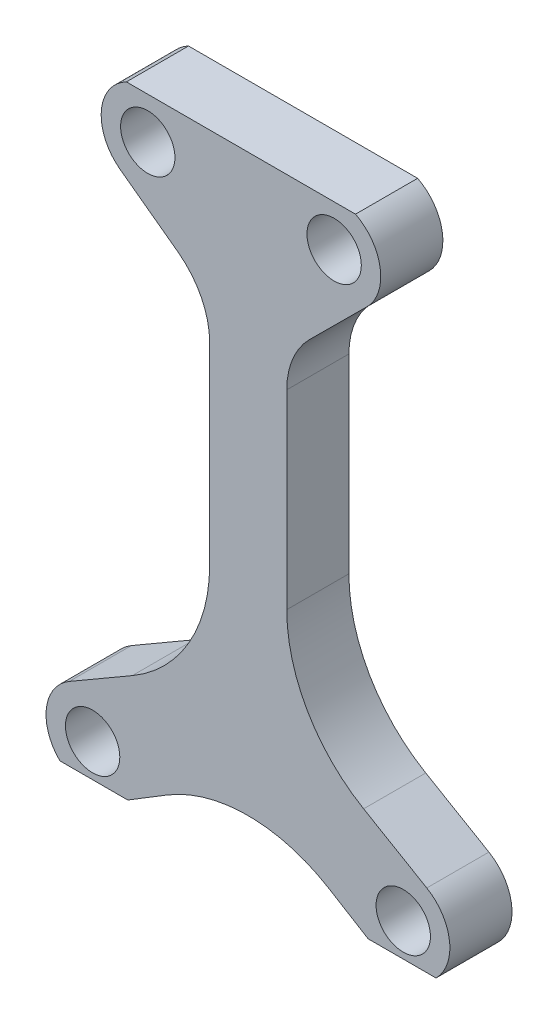
SolidWorks part; units mm, degrees
ref_plane "前视基准面" through (0, 0, 0) normal (0, 0, 1) x (1, 0, 0)
ref_plane "上视基准面" through (0, 0, 0) normal (0, 1, 0) x (1, 0, 0)
ref_plane "右视基准面" through (0, 0, 0) normal (1, 0, 0) x (0, 0, -1)
sketch "草图1" plane through (0, 0, 0) normal (0, 0, 1) x (1, 0, 0)
  line L1 (0, 0) -> (28, 0)
  line L2 (0, 0) -> (0, 40)
  line L3 (0, 40) -> (28, 40)
  line L4 (28, 0) -> (28, 40)
  dimension "D1" = 28
  dimension "D2" = 40
extrude "凸台-拉伸1" add sketch "草图1" along normal blind 4
sketch "草图2" plane through (0, 0, 4) normal (0, 0, 1) x (1, 0, 0)
  line L1 (7.55, 35.3346) -> (19.55, 35.3346) construction
  line L2 (7.55, 37.3346) -> (19.55, 37.3346) construction
  circle A0 centre (7.55, 35.3346) radius 1.75 construction
  circle A1 centre (19.55, 35.3346) radius 1.75 construction
  circle A2 centre (4, 2.1346) radius 1.75
  circle A3 centre (24, 2.1346) radius 1.75
  circle A5 centre (19.55, 37.3346) radius 1.75
  circle A6 centre (7.55, 37.3346) radius 1.75
  dimension "D1" = 3.5
  dimension "D2" = 3.5
  dimension "D3" = 3.5
  dimension "D4" = 3.5
  dimension "D6" = 3.5
  dimension "D7" = 3.5
  dimension "D5" = 2
extrude "切除-拉伸1" cut sketch "草图2" against normal through all
sketch "草图3" plane through (0, 0, 4) normal (0, 0, 1) x (1, 0, 0)
  line L0 (14, 40) -> (14, 0) construction
  line L2 (11.5361, 28.1453) -> (11.5361, 15.7342)
  line L4 (16.5, 27.9927) -> (16.5, 15.7342)
  line L5 (28, 40) -> (0, 40) construction
  line L6 (0, 0) -> (28, 0) construction
  line L7 (5.7708, 34.9191) -> (9.5015, 32.171)
  line L8 (17.9749, 31.5386) -> (21.665, 35.207)
  line L9 (6.5538, 7.0842) -> (2.4947, 4.7296)
  line L10 (21.4489, 7.1036) -> (25.5153, 4.7237)
  line L11 (7.55, 40.3346) -> (19.55, 40.3346)
  line L12 (5.563, -0.4261) -> (8.79, 1.5436)
  line L13 (19.21, 1.5436) -> (22.437, -0.4261)
  line L15 (-7.3505, 44.0109) -> (39.4057, 44.0109)
  line L16 (-7.3505, 44.0109) -> (-7.3505, -4.9101)
  line L17 (-7.3505, -4.9101) -> (39.4057, -4.9101)
  line L18 (39.4057, 44.0109) -> (39.4057, -4.9101)
  arc A0 (2.4947, 4.7296) -> (5.563, -0.4261) centre (4, 2.1346) ccw
  arc A1 (22.437, -0.4261) -> (25.5153, 4.7237) centre (24, 2.1346) ccw
  arc A2 (7.55, 40.3346) -> (5.7708, 34.9191) centre (7.55, 37.3346) ccw
  arc A3 (21.665, 35.207) -> (19.55, 40.3346) centre (19.55, 37.3346) ccw
  arc A4 (8.79, 1.5436) -> (19.21, 1.5436) centre (14, -6.992) cw
  arc A5 (11.5361, 15.7342) -> (6.5538, 7.0842) centre (1.5361, 15.7342) cw
  arc A6 (21.4489, 7.1036) -> (16.5, 15.7342) centre (26.5, 15.7342) cw
  arc A7 (17.9749, 31.5386) -> (16.5, 27.9927) centre (21.5, 27.9927) ccw
  arc A8 (11.5361, 28.1453) -> (9.5015, 32.171) centre (6.5361, 28.1453) ccw
  point P32 (14, 4.7237)
  point P39 (16.5, 30.0724)
  point P42 (11.5361, 30.6723)
  dimension "D1" = 6
  dimension "D2" = 6
  dimension "D3" = 6
  dimension "D4" = 6
  dimension "D7" = 10
  dimension "D8" = 10
  dimension "D9" = 10
  dimension "D10" = 5
  dimension "D5" = 5
  dimension "D6" = 2.5
extrude "切除-拉伸2" cut sketch "草图3" against normal through all
